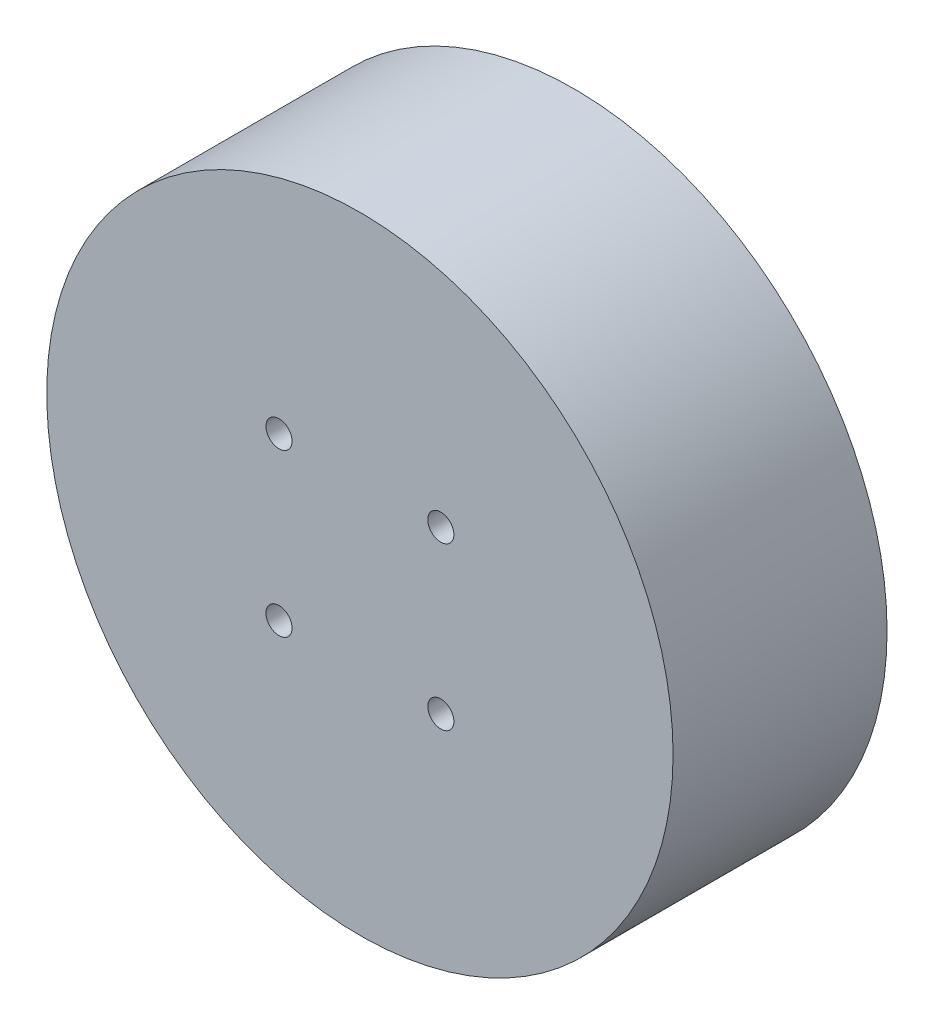
SolidWorks part; units mm, degrees
ref_plane "Front Plane" through (0, 0, 0) normal (0, 0, 1) x (1, 0, 0)
ref_plane "Top Plane" through (0, 0, 0) normal (0, 1, 0) x (1, 0, 0)
ref_plane "Right Plane" through (0, 0, 0) normal (1, 0, 0) x (0, 0, -1)
sketch "Sketch1" plane through (0, 0, 0) normal (0, 0, 1) x (1, 0, 0)
  circle A0 centre (0, 0) radius 60
  dimension "D1" = 120
extrude "Boss-Extrude1" add sketch "Sketch1" along normal mid plane 41
sketch "Sketch2" plane through (0, 0, 20.5) normal (0, 0, 1) x (1, 0, 0)
  line L1 (-15.5, -15.5) -> (15.5, -15.5) construction
  line L2 (-15.5, -15.5) -> (-15.5, 15.5) construction
  line L3 (-15.5, 15.5) -> (15.5, 15.5) construction
  line L4 (15.5, -15.5) -> (15.5, 15.5) construction
  line L5 (-15.5, -15.5) -> (15.5, 15.5) construction
  line L6 (-15.5, 15.5) -> (15.5, -15.5) construction
  circle A0 centre (-15.5, 15.5) radius 2.5
  circle A1 centre (15.5, 15.5) radius 2.5
  circle A2 centre (15.5, -15.5) radius 2.5
  circle A3 centre (-15.5, -15.5) radius 2.5
  point P0 (0, 0)
  dimension "D2" = 5
  dimension "D1" = 31
  dimension "D3" = 2
  dimension "D4" = 2
extrude "Cut-Extrude1" cut sketch "Sketch2" against normal blind 10
